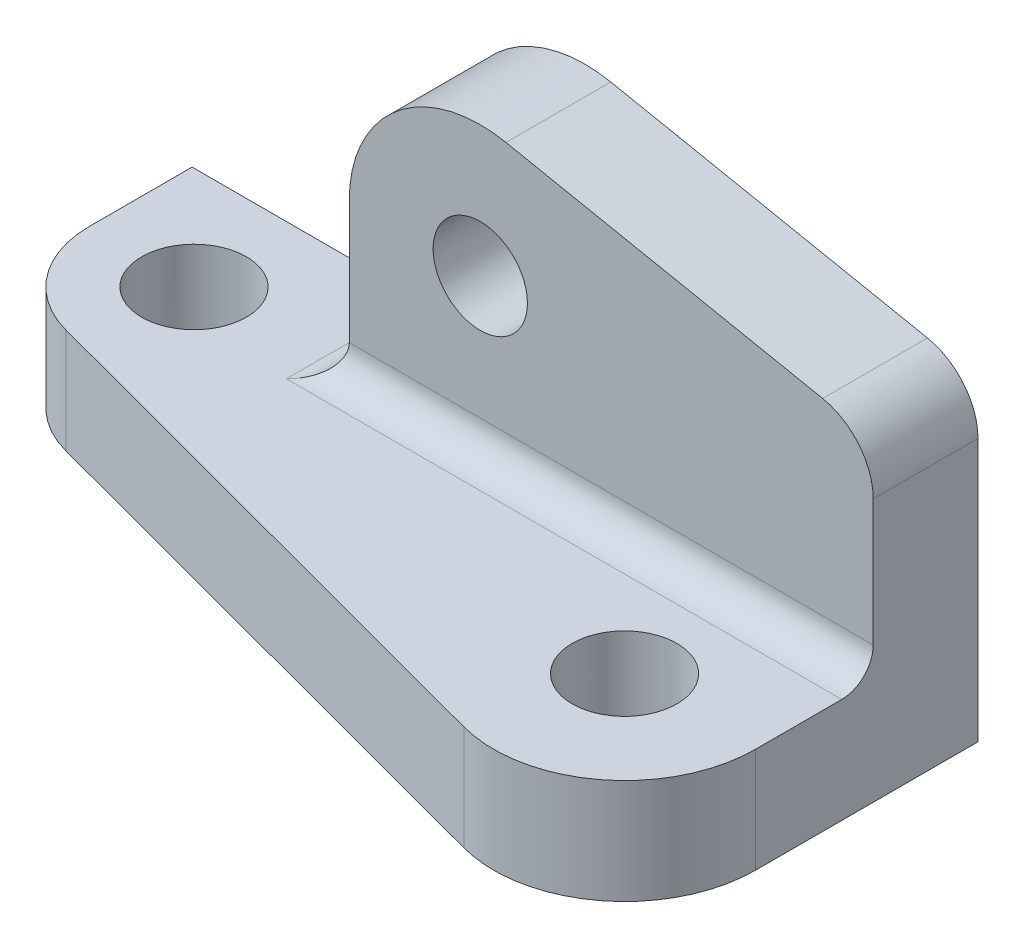
SolidWorks part; units mm, degrees
material "Magnesium Alloy"
ref_plane "Front Plane" through (0, 0, 0) normal (0, 0, 1) x (1, 0, 0)
ref_plane "Top Plane" through (0, 0, 0) normal (0, 1, 0) x (1, 0, 0)
ref_plane "Right Plane" through (0, 0, 0) normal (1, 0, 0) x (0, 0, -1)
sketch "Sketch1" plane through (0, 0, 0) normal (0, 1, 0) x (1, 0, 0)
  line L0 (0, 0) -> (0, -75)
  line L1 (0, -75) -> (-150, -35)
  line L2 (-150, -35) -> (-150, 0)
  line L3 (-150, 0) -> (0, 0)
  dimension "D1" = 150
  dimension "D2" = 35
  dimension "D3" = 75
extrude "Boss-Extrude1" add sketch "Sketch1" along normal blind 20
sketch "Sketch2" plane through (0, 0, 0) normal (0, 0, -1) x (-1, 0, 0)
  line L0 (0, 0) -> (0, 60)
  line L1 (0, 60) -> (100, 80)
  line L2 (100, 80) -> (100, 0)
  line L3 (0, 0) -> (150, 0) construction
  line L4 (100, 0) -> (0, 0)
  dimension "D1" = 100
  dimension "D2" = 60
  dimension "D3" = 80
extrude "Boss-Extrude2" add sketch "Sketch2" against normal blind 20
fillet "Fillet1" radius 12 1 edges at (0, 60, 10)
fillet "Fillet2" radius 20 1 edges at (-150, 10, 35)
fillet "Fillet3" radius 25 2 edges at (-100, 80, 10) (0, 10, 75)
fillet "Fillet4" radius 6 2 edges at (-100, 20, 10) (-50, 20, 20)
hole_wizard "Ø1.0 mm Dowel Holes1" positions "Sketch3" profile "Sketch4" hole size "Ø1.0" standard "ANSI Metric" end condition up to next
sketch "Sketch3" plane through (0, 20, 0) normal (0, 1, 0) x (1, 0, 0)
  point P0 (-130, -19.6344)
  point P3 (-25, -42.4597)
sketch "Sketch4" plane through (-130, 20, 19.6344) normal (1, 0, 0) x (0, 0, 1)
  line L0 (0, 0) -> (0, 20)
  line L1 (0, 20) -> (10, 20)
  line L2 (10, 20) -> (10, 0)
  line L5 (10, 0) -> (0, 0)
  line L11 (0, -6.35) -> (0, 107.95) construction
  dimension "Thru Hole Dia." = 20
  dimension "Thru Hole Depth" = 20
hole_wizard "Ø1.0 mm Dowel Holes2" positions "Sketch5" profile "Sketch6" hole size "Ø1.0" standard "ANSI Metric" end condition up to next
sketch "Sketch5" plane through (0, 0, 20) normal (0, 0, 1) x (1, 0, 0)
  point P0 (-75, 49.5049)
sketch "Sketch6" plane through (-75, 49.5049, 20) normal (1, 0, 0) x (0, -1, 0)
  line L0 (0, 0) -> (0, 20)
  line L1 (0, 20) -> (9, 20)
  line L2 (9, 20) -> (9, 0)
  line L5 (9, 0) -> (0, 0)
  line L11 (0, -6.35) -> (0, 107.95) construction
  dimension "Thru Hole Dia." = 18
  dimension "Thru Hole Depth" = 20
